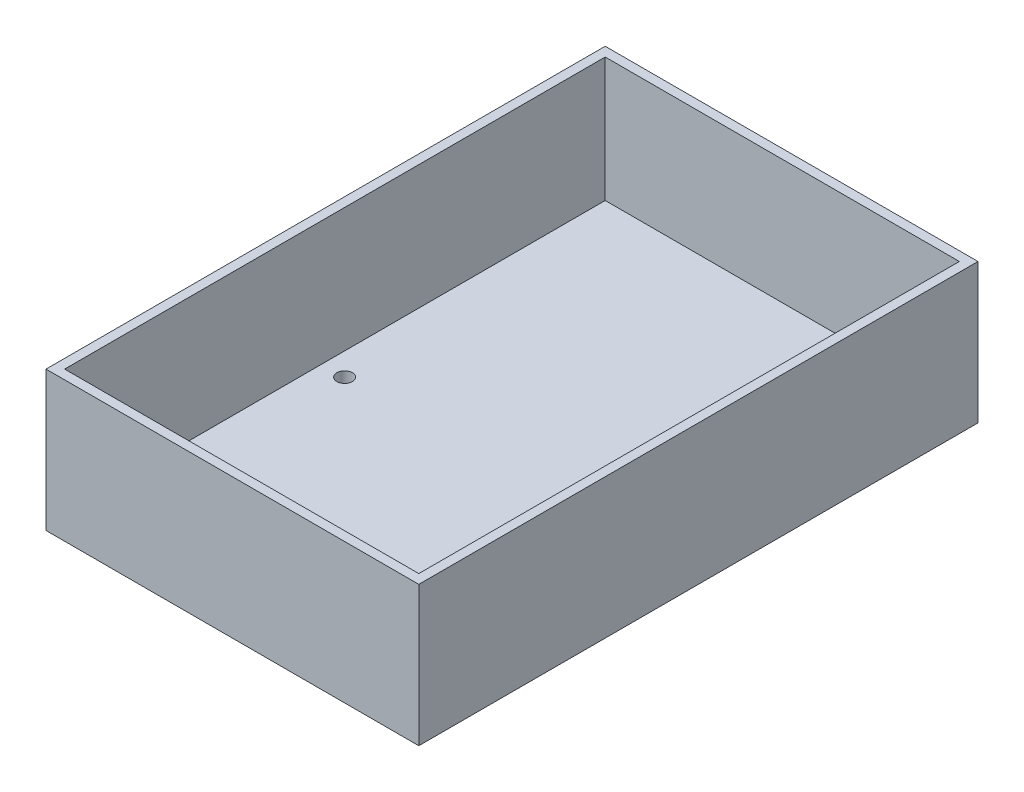
SolidWorks part; units mm, degrees
ref_plane "Front Plane" through (0, 0, 0) normal (0, 0, 1) x (1, 0, 0)
ref_plane "Top Plane" through (0, 0, 0) normal (0, 1, 0) x (1, 0, 0)
ref_plane "Right Plane" through (0, 0, 0) normal (1, 0, 0) x (0, 0, -1)
sketch "Sketch1" plane through (0, 0, 0) normal (0, 1, 0) x (1, 0, 0)
  line L1 (0, 0) -> (120, 0)
  line L2 (0, 0) -> (0, 180)
  line L3 (0, 180) -> (120, 180)
  line L4 (120, 0) -> (120, 180)
  dimension "D1" = 120
  dimension "D2" = 180
extrude "Boss-Extrude1" add sketch "Sketch1" along normal blind 45
sketch "Sketch3" plane through (0, 45, 0) normal (0, 1, 0) x (1, 0, 0)
  line L8 (3, 177) -> (3, 3)
  line L9 (3, 3) -> (117, 3)
  line L10 (117, 3) -> (117, 177)
  line L11 (117, 177) -> (3, 177)
  line L12 (3, 177) -> (3, 3)
  line L13 (3, 3) -> (117, 3)
  line L14 (117, 3) -> (117, 177)
  line L15 (117, 177) -> (3, 177)
  dimension "D1" = 3
extrude "Cut-Extrude1" cut sketch "Sketch3" against normal blind 40
sketch "Sketch4" plane through (0, 5, 0) normal (0, 1, 0) x (1, 0, 0)
  line L0 (3, 3) -> (117, 3) construction
  line L1 (3, 177) -> (3, 3) construction
  line L2 (117, 3) -> (117, 177) construction
  circle A0 centre (10.3, 85.8186) radius 2.5
  circle A1 centre (60, 7) radius 2.5
  dimension "D3" = 5
  dimension "D6" = 5
  dimension "D1" = 82.8186
  dimension "D2" = 7.3
  dimension "D4" = 4
  dimension "D5" = 57
extrude "Cut-Extrude2" cut sketch "Sketch4" against normal blind 5
sketch "Sketch5" plane through (0, 5, 0) normal (0, 1, 0) x (1, 0, 0)
  line L0 (3, 3) -> (117, 3) construction
  line L1 (117, 3) -> (117, 177) construction
  line L2 (3, 3) -> (117, 3) construction
  circle A0 centre (99, 79) radius 2.5
  circle A1 centre (99, 15) radius 2.5
  point P8 (0, 0)
  point P11 (0, 0)
  point P12 (0, 0)
  point P13 (0, 0)
  point P14 (0, 0)
  dimension "D1" = 76
  dimension "D2" = 18
  dimension "D3" = 5
  dimension "D4" = 12
  dimension "D5" = 18
  dimension "D6" = 5
